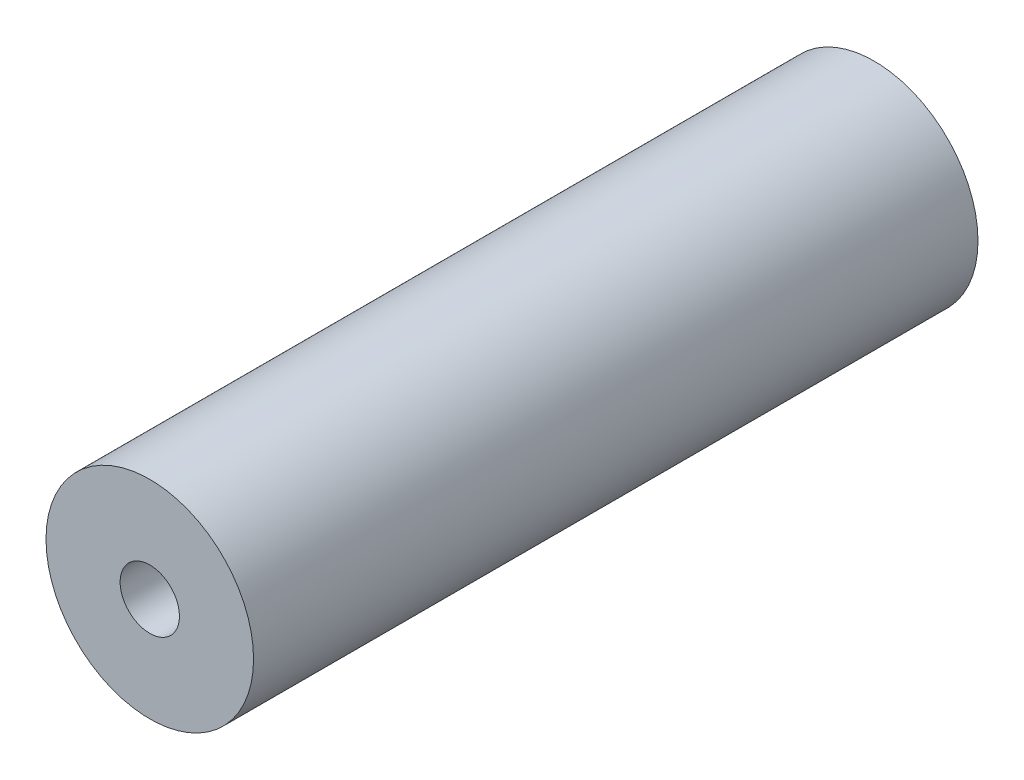
SolidWorks part; units mm, degrees
ref_plane "Front Plane" through (0, 0, 0) normal (0, 0, 1) x (1, 0, 0)
ref_plane "Top Plane" through (0, 0, 0) normal (0, 1, 0) x (1, 0, 0)
ref_plane "Right Plane" through (0, 0, 0) normal (1, 0, 0) x (0, 0, -1)
sketch "Sketch1" plane through (0, 0, 0) normal (0, 0, 1) x (1, 0, 0)
  circle A0 centre (0, 0) radius 3.175
  circle A1 centre (0, 0) radius 11.1125
  dimension "D1" = 22.225
  dimension "D2" = 6.35
extrude "Boss-Extrude1" add sketch "Sketch1" along normal blind 77.5716
